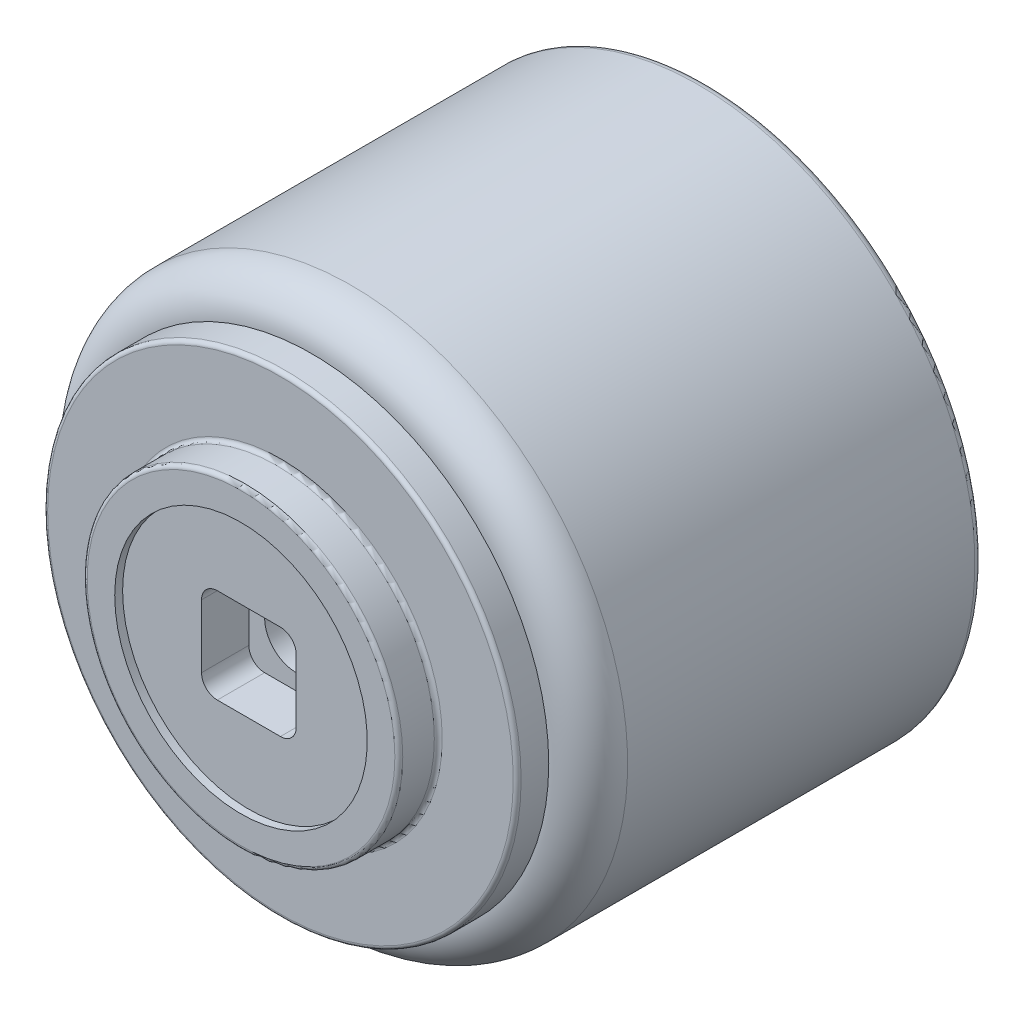
SolidWorks part; units mm, degrees
ref_plane "Front Plane" through (0, 0, 0) normal (0, 0, 1) x (1, 0, 0)
ref_plane "Top Plane" through (0, 0, 0) normal (0, 1, 0) x (1, 0, 0)
ref_plane "Right Plane" through (0, 0, 0) normal (1, 0, 0) x (0, 0, -1)
ref_plane "Plane1" through (0, 0, 0) normal (0, -1, 0) x (1, 0, 0)
sketch "Sketch1" plane through (0, 0, 0) normal (0, -1, 0) x (1, 0, 0)
  line L0 (30, 54) -> (0, 54)
  line L1 (0, 54) -> (0, 0)
  line L2 (0, 0) -> (35, 0)
  line L3 (35, 0) -> (35, 45)
  line L4 (30, 50) -> (30, 54)
  line L5 (0, 54) -> (0, 0) construction
  arc A0 (35, 45) -> (30, 50) centre (30, 45) ccw
revolve "Revolve1" add sketch "Sketch1" angle 360 about L5
sketch "Sketch2" plane through (0, 0, 54) normal (0, 0, 1) x (1, 0, 0)
  circle A0 centre (0, 0) radius 20
extrude "Boss-Extrude1" add sketch "Sketch2" along normal blind 5
sketch "Sketch3" plane through (0, 0, 59) normal (0, 0, 1) x (1, 0, 0)
  line L0 (-6, 6) -> (-6, -6)
  line L1 (-6, -6) -> (6, -6)
  line L2 (6, -6) -> (6, 6)
  line L3 (6, 6) -> (-6, 6)
extrude "Cut-Extrude1" cut sketch "Sketch3" against normal blind 7
hole_wizard "M45 Clearance Hole1" positions "Sketch5" profile "Sketch4" hole size "M45" standard "ANSI Metric"
sketch "Sketch5" plane through (0, 0, 0) normal (0, 0, -1) x (-1, 0, 0)
  point P0 (0, 0)
sketch "Sketch4" plane through (0, 0, 0) normal (1, 0, 0) x (0, 1, 0)
  line L0 (0, 0) -> (0, 3)
  line L1 (0, 3) -> (25, 3)
  line L2 (25, 3) -> (25, 0)
  line L5 (25, 0) -> (0, 0)
  line L10 (0, 3) -> (-25, 3) construction
  line L11 (0, -6.35) -> (0, 107.95) construction
  dimension "Hole Dia." = 50
  dimension "Hole Depth" = 3
  dimension "Drill Angle" = 180
sketch "Sketch6" plane through (0, 0, 0) normal (0, 1, 0) x (1, 0, 0)
  line L0 (12.5, -1) -> (0, -1)
  line L1 (0, -1) -> (0, -3)
  line L2 (0, -3) -> (12.5, -3)
  line L3 (12.5, -3) -> (12.5, -1)
  line L4 (0, -1) -> (0, -3) construction
revolve "Revolve2" add sketch "Sketch6" angle 360 about L4
sketch "Sketch7" plane through (0, 0, 0) normal (0, 1, 0) x (1, 0, 0)
  line L0 (-16, -59) -> (0, -59)
  line L1 (0, -59) -> (0, -58)
  line L2 (0, -58) -> (-16, -58)
  line L3 (-16, -58) -> (-16, -59)
  line L4 (0, -59) -> (0, -58) construction
revolve "Cut-Revolve1" cut sketch "Sketch7" angle 360 about L4
hole_wizard "Ø8.0 (8) Diameter Hole1" positions "Sketch9" profile "Sketch8" hole size "Ø8.0" standard "ANSI Metric"
sketch "Sketch9" plane through (0, 0, 52) normal (0, 0, 1) x (1, 0, 0)
  point P0 (0, 0)
sketch "Sketch8" plane through (0, 0, 52) normal (1, 0, 0) x (0, -1, 0)
  line L0 (0, 0) -> (0, 52)
  line L1 (0, 52) -> (4, 52)
  line L2 (4, 52) -> (4, 0)
  line L5 (4, 0) -> (0, 0)
  line L11 (0, -6.35) -> (0, 107.95) construction
  dimension "Thru Hole Dia." = 8
  dimension "Thru Hole Depth" = 52
fillet "Fillet1" radius 0.5 7 edges at (-30, 0, 54) (12.5, 0, 1) (-25, 0, 0) (20, 0, 54) (-25, 0, 3) (20, 0, 59) (12.5, 0, 3)
fillet "Fillet2" radius 1 1 edges at (-35, 0, 0)
fillet "Fillet3" radius 2 4 edges at (-6, -6, 55) (6, -6, 55) (-6, 6, 55) (6, 6, 55)
